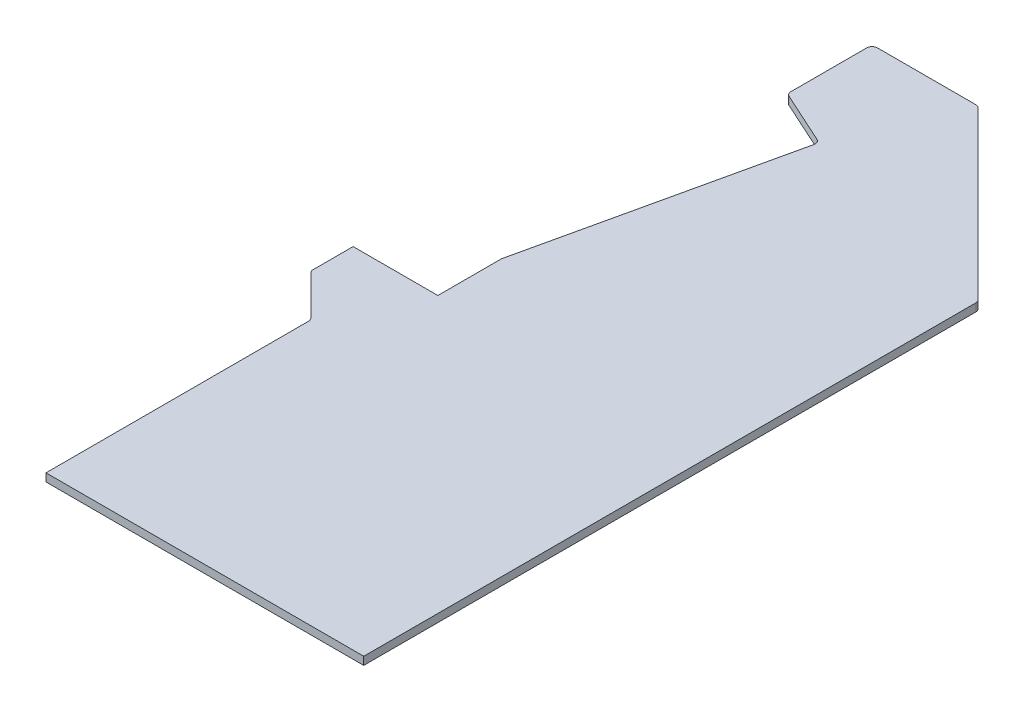
SolidWorks part; units mm, degrees
ref_plane "Front Plane" through (0, 0, 0) normal (0, 0, 1) x (1, 0, 0)
ref_plane "Top Plane" through (0, 0, 0) normal (0, 1, 0) x (1, 0, 0)
ref_plane "Right Plane" through (0, 0, 0) normal (1, 0, 0) x (0, 0, -1)
sketch "Sketch1" plane through (0, 0, 0) normal (0, 1, 0) x (1, 0, 0)
  line L0 (-108.5345, -3.9032) -> (-108.5345, 1464.0363)
  line L1 (-108.5345, -3.9032) -> (-870.5345, -3.9032)
  line L2 (-870.5345, -3.9032) -> (-870.5345, 625.8363)
  line L3 (-972.1345, 737.9573) -> (-972.1345, 834.2968)
  line L4 (-768.9345, 834.2968) -> (-768.9345, 986.6968)
  line L5 (-972.1345, 834.2968) -> (-768.9345, 834.2968)
  line L7 (-968.4148, 728.977) -> (-874.2542, 634.8165)
  line L9 (-520.195, 1875.6968) -> (-756.2345, 1875.6968)
  line L10 (-112.2542, 1473.0165) -> (-511.2148, 1871.977)
  line L14 (-761.4898, 1669.1128) -> (-638.6318, 1613.2683)
  line L15 (-631.4955, 1598.9249) -> (-768.9345, 986.6968)
  line L16 (-768.9345, 1680.6745) -> (-768.9345, 1862.9968)
  arc A0 (-108.5345, 1464.0363) -> (-112.2542, 1473.0165) centre (-121.2345, 1464.0363) ccw
  arc A1 (-511.2148, 1871.977) -> (-520.195, 1875.6968) centre (-520.195, 1862.9968) ccw
  arc A2 (-768.9345, 1862.9968) -> (-756.2345, 1875.6968) centre (-756.2345, 1862.9968) cw
  arc A3 (-768.9345, 1680.6745) -> (-761.4898, 1669.1128) centre (-756.2345, 1680.6745) ccw
  arc A4 (-631.4955, 1598.9249) -> (-638.6318, 1613.2683) centre (-643.8871, 1601.7067) ccw
  arc A5 (-972.1345, 737.9573) -> (-968.4148, 728.977) centre (-959.4345, 737.9573) ccw
  arc A6 (-870.5345, 625.8363) -> (-874.2542, 634.8165) centre (-883.2345, 625.8363) ccw
  dimension "D1" = 12.7
extrude "Boss-Extrude1" add sketch "Sketch1" along normal blind 19.05
